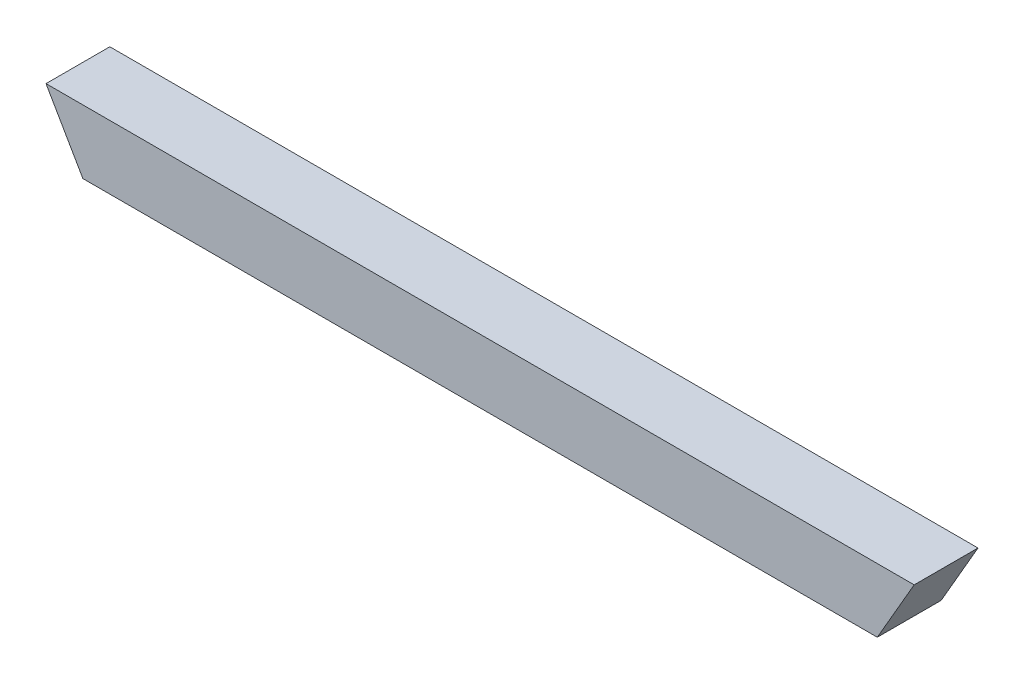
SolidWorks part; units mm, degrees
ref_plane "Front Plane" through (0, 0, 0) normal (0, 0, 1) x (1, 0, 0)
ref_plane "Top Plane" through (0, 0, 0) normal (0, 1, 0) x (1, 0, 0)
ref_plane "Right Plane" through (0, 0, 0) normal (1, 0, 0) x (0, 0, -1)
sketch "Sketch1" plane through (0, 0, 0) normal (0, 0, 1) x (1, 0, 0)
  line L0 (-67.6667, 34.8333) -> (204.4033, 34.8333)
  line L1 (204.4033, 34.8333) -> (192.8483, 14.8333)
  line L2 (192.8483, 14.8333) -> (-56.1117, 14.8333)
  line L3 (-56.1117, 14.8333) -> (-67.6667, 34.8333)
  point P2 (68.3683, 34.8333)
  point P5 (68.3683, 14.8333)
  dimension "D1" = 20
  dimension "D2" = 272.07
  dimension "D3" = 248.96
extrude "Boss-Extrude1" add sketch "Sketch1" along normal blind 20
